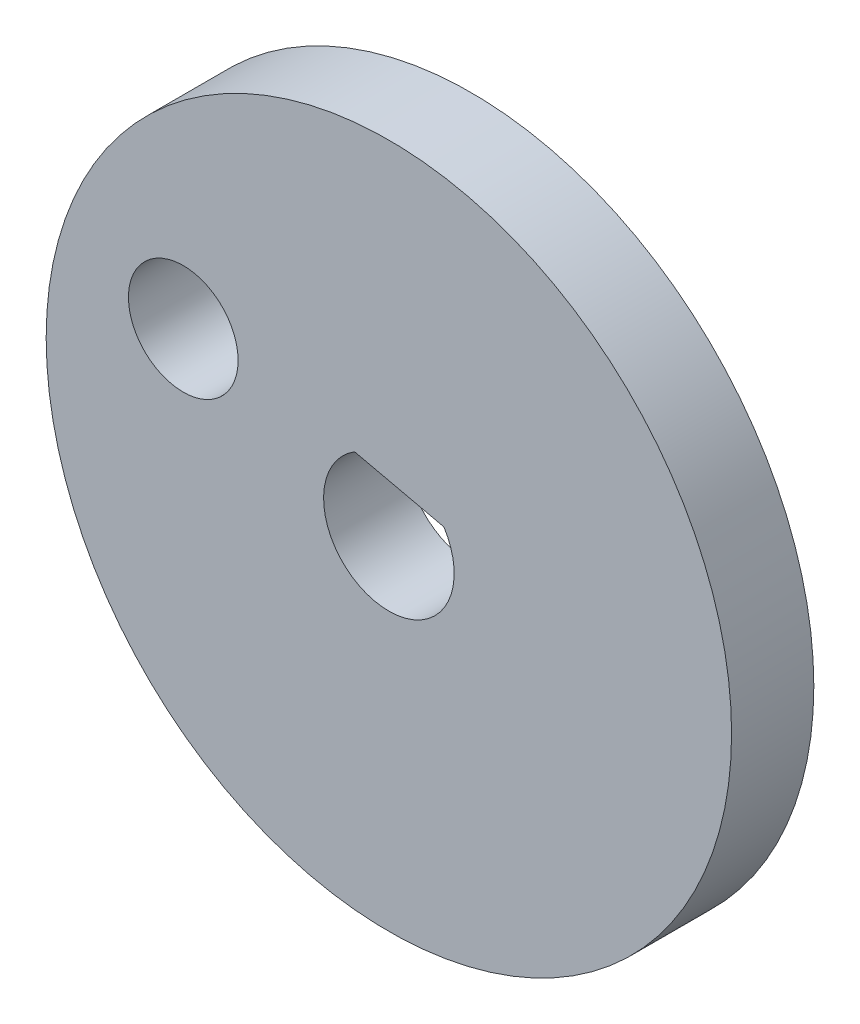
SolidWorks part; units mm, degrees
ref_plane "Front Plane" through (0, 0, 0) normal (0, 0, 1) x (1, 0, 0)
ref_plane "Top Plane" through (0, 0, 0) normal (0, 1, 0) x (1, 0, 0)
ref_plane "Right Plane" through (0, 0, 0) normal (1, 0, 0) x (0, 0, -1)
sketch "Sketch1" plane through (0, 0, 0) normal (0, 0, 1) x (1, 0, 0)
  circle A0 centre (0, 0) radius 12.5
  dimension "D1" = 25
extrude "Boss-Extrude1" add sketch "Sketch1" along normal blind 3
sketch "Sketch2" plane through (0, 0, 3) normal (0, 0, 1) x (1, 0, 0)
  line L0 (-1.2492, 2.0273) -> (2.0067, 1.282)
  arc A0 (-1.2492, 2.0273) -> (2.0067, 1.282) centre (0, 0) ccw
  dimension "D1" = 4.7625
  dimension "D2" = 2.0067
  dimension "D3" = 3.3401
extrude "Cut-Extrude1" cut sketch "Sketch2" against normal blind 3 contours A0 L0
sketch "Sketch3" plane through (0, 0, 3) normal (0, 0, 1) x (1, 0, 0)
  circle A0 centre (-7.4992, 2.7862) radius 2
  circle A2 centre (0, 0) radius 12.5 construction
  point P4 (-8.3622, 3.1068)
  dimension "D1" = 4
  dimension "D2" = 8
extrude "Cut-Extrude2" cut sketch "Sketch3" against normal blind 3 contours A0
equation "\"outer_diameter_spool\"= 25"
equation "\"D1@Sketch1\"=\"outer_diameter_spool\""
equation "\"depth\"=3"
equation "\"D1@Boss-Extrude1\"=\"depth\""
equation "\"laser_offset\"= 0.125"
equation "\"diameter_shaft\"=4.7625"
equation "\"D1@Sketch2\"=\"diameter_shaft\""
equation "\"D1@Cut-Extrude1\"= \"depth\""
equation "\"hole_diameter\"=4"
equation "\"D1@Sketch3\"=\"hole_diameter\""
equation "\"dist_hole\"=8"
equation "\"D2@Sketch3\"=\"dist_hole\""
equation "\"D1@Cut-Extrude2\"= \"depth\""
